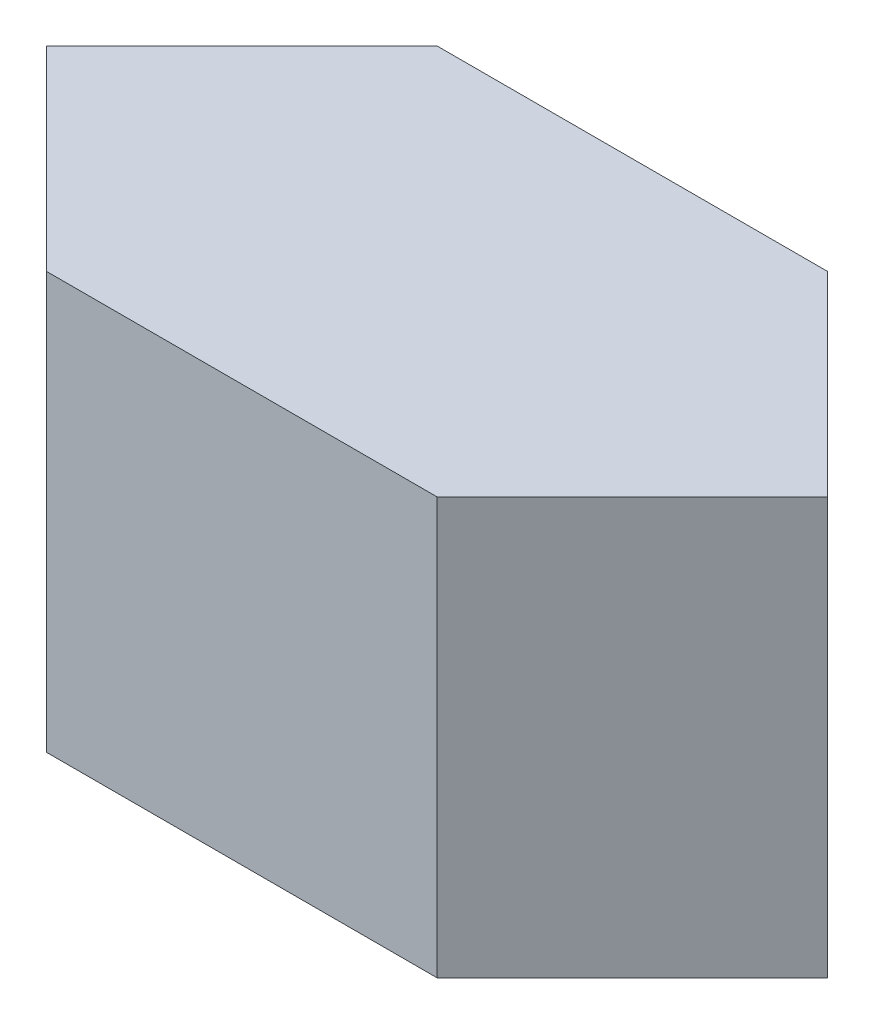
SolidWorks part; units mm, degrees
ref_plane "Front Plane" through (0, 0, 0) normal (0, 0, 1) x (1, 0, 0)
ref_plane "Top Plane" through (0, 0, 0) normal (0, 1, 0) x (1, 0, 0)
ref_plane "Right Plane" through (0, 0, 0) normal (1, 0, 0) x (0, 0, -1)
sketch "Sketch1" plane through (0, 0, 0) normal (0, 1, 0) x (1, 0, 0)
  line L0 (15, 15) -> (30, -0.0187)
  line L5 (15, 15) -> (-15, 15)
  line L6 (15, 15) -> (15, -15)
  line L7 (15, -15) -> (-15, -15)
  line L8 (-15, 15) -> (-15, -15)
  line L9 (15, 15) -> (-15, -15) construction
  line L10 (15, -15) -> (-15, 15) construction
  line L11 (30, -0.0187) -> (15, -15)
  line L12 (0, 15) -> (0, -15) construction
  line L13 (-30, -0.0187) -> (-15, -15)
  line L14 (-15, 15) -> (-30, -0.0187)
  point P0 (0, 0)
  dimension "D3" = 15
  dimension "D4" = 90
  dimension "D1" = 30
  dimension "D2" = 21.2
extrude "Boss-Extrude2" add sketch "Sketch1" along normal blind 32 contours L8 L14 L13 | L5 L8 L7 L6 | L11 L0 L6
